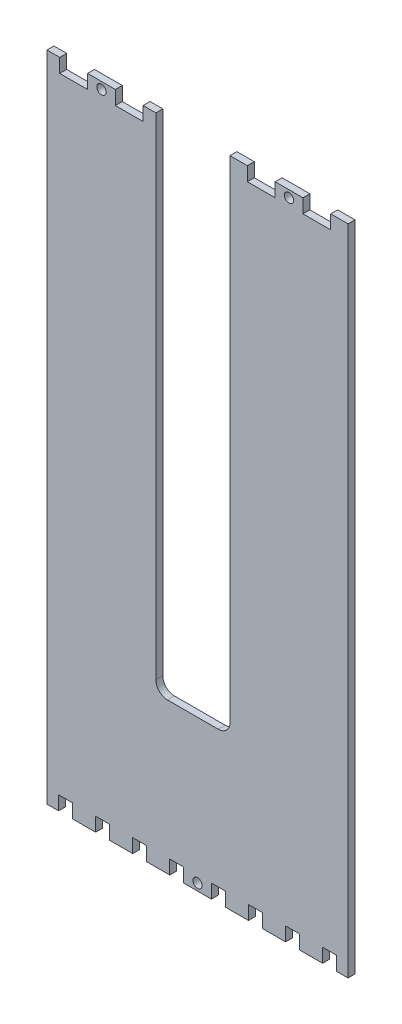
SolidWorks part; units mm, degrees
ref_plane "Plan de face" through (0, 0, 0) normal (0, 0, 1) x (1, 0, 0)
ref_plane "Plan de dessus" through (0, 0, 0) normal (0, 1, 0) x (1, 0, 0)
ref_plane "Plan de droite" through (0, 0, 0) normal (1, 0, 0) x (0, 0, -1)
sketch "Esquisse1" plane through (0, 0, 0) normal (0, 0, 1) x (1, 0, 0)
  line L1 (-46.5414, 49.7197) -> (83.4586, 49.7197)
  line L2 (-46.5414, 49.7197) -> (-46.5414, -232.2803)
  line L3 (-46.5414, -232.2803) -> (83.4586, -232.2803)
  line L4 (83.4586, 49.7197) -> (83.4586, -232.2803)
  dimension "D1" = 130
  dimension "D2" = 282
extrude "Boss.-Extru.1" add sketch "Esquisse1" along normal blind 3
sketch "Esquisse2" plane through (0, 0, 3) normal (0, 0, 1) x (1, 0, 0)
  line L0 (-46.5414, 49.7197) -> (-46.5414, -232.2803) construction
  line L1 (32.4586, -167.2803) -> (0.4586, -167.2803)
  line L2 (32.4586, -167.2803) -> (32.4586, 49.7197)
  line L3 (32.4586, 49.7197) -> (0.4586, 49.7197)
  line L4 (0.4586, -167.2803) -> (0.4586, 49.7197)
  line L5 (83.4586, -232.2803) -> (83.4586, 49.7197) construction
  line L6 (-46.5414, -232.2803) -> (83.4586, -232.2803) construction
  line L7 (83.4586, 49.7197) -> (-46.5414, 49.7197) construction
  dimension "D1" = 47
  dimension "D2" = 51
  dimension "D3" = 65
  dimension "D4" = 0
extrude "Enlèv. mat.-Extru.1" cut sketch "Esquisse2" against normal blind 3
fillet "Congé1" radius 5 2 edges at (32.4586, -167.2803, 1.5) (0.4586, -167.2803, 1.5)
sketch "Esquisse3" plane through (0, 0, 3) normal (0, 0, 1) x (1, 0, 0)
  line L0 (-23.0414, 49.7197) -> (-23.0414, 37.8262) construction
  line L1 (0.4586, 49.7197) -> (-46.5414, 49.7197) construction
  line L2 (-29.0414, 46.7197) -> (-17.0414, 46.7197) construction
  line L3 (-29.0414, 49.7197) -> (-41.0414, 49.7197)
  line L4 (-29.0414, 49.7197) -> (-29.0414, 43.7197)
  line L5 (-29.0414, 43.7197) -> (-41.0414, 43.7197)
  line L6 (-41.0414, 49.7197) -> (-41.0414, 43.7197)
  line L7 (-17.0414, 49.7197) -> (-5.0414, 49.7197)
  line L8 (-17.0414, 49.7197) -> (-17.0414, 43.7197)
  line L9 (-17.0414, 43.7197) -> (-5.0414, 43.7197)
  line L10 (-5.0414, 49.7197) -> (-5.0414, 43.7197)
  line L11 (-17.0414, 43.7197) -> (109.581, 43.7197) construction
  line L12 (57.9586, 49.7197) -> (57.9586, 43.7197) construction
  line L13 (83.4586, 49.7197) -> (32.4586, 49.7197) construction
  line L14 (51.9586, 46.7197) -> (63.9586, 46.7197) construction
  line L15 (51.9586, 49.7197) -> (39.9586, 49.7197)
  line L16 (51.9586, 49.7197) -> (51.9586, 43.7197)
  line L17 (51.9586, 43.7197) -> (39.9586, 43.7197)
  line L18 (39.9586, 49.7197) -> (39.9586, 43.7197)
  line L19 (63.9586, 49.7197) -> (75.9586, 49.7197)
  line L20 (63.9586, 49.7197) -> (63.9586, 43.7197)
  line L21 (63.9586, 43.7197) -> (75.9586, 43.7197)
  line L22 (75.9586, 49.7197) -> (75.9586, 43.7197)
  line L23 (18.4586, -232.2803) -> (18.4586, -214.6987) construction
  line L24 (-46.5414, -232.2803) -> (83.4586, -232.2803) construction
  line L25 (-46.5414, -226.2803) -> (83.4586, -226.2803) construction
  line L26 (-46.5414, 49.7197) -> (-46.5414, -232.2803) construction
  line L27 (83.4586, -232.2803) -> (83.4586, 49.7197) construction
  line L28 (12.4586, -229.2803) -> (24.4586, -229.2803) construction
  line L29 (12.4586, -232.2803) -> (6.4586, -232.2803)
  line L30 (12.4586, -232.2803) -> (12.4586, -226.2803)
  line L31 (12.4586, -226.2803) -> (6.4586, -226.2803)
  line L32 (6.4586, -232.2803) -> (6.4586, -226.2803)
  line L33 (-3.5414, -232.2803) -> (-9.5414, -232.2803)
  line L34 (-3.5414, -232.2803) -> (-3.5414, -226.2803)
  line L35 (-3.5414, -226.2803) -> (-9.5414, -226.2803)
  line L36 (-9.5414, -232.2803) -> (-9.5414, -226.2803)
  line L37 (-35.5414, -232.2803) -> (-41.5414, -232.2803)
  line L38 (-35.5414, -232.2803) -> (-35.5414, -226.2803)
  line L39 (-35.5414, -226.2803) -> (-41.5414, -226.2803)
  line L40 (-41.5414, -232.2803) -> (-41.5414, -226.2803)
  line L41 (24.4586, -232.2803) -> (30.4586, -232.2803)
  line L42 (24.4586, -232.2803) -> (24.4586, -226.2803)
  line L43 (24.4586, -226.2803) -> (30.4586, -226.2803)
  line L44 (30.4586, -232.2803) -> (30.4586, -226.2803)
  line L45 (40.4586, -232.2803) -> (46.4586, -232.2803)
  line L46 (40.4586, -232.2803) -> (40.4586, -226.2803)
  line L47 (40.4586, -226.2803) -> (46.4586, -226.2803)
  line L48 (46.4586, -232.2803) -> (46.4586, -226.2803)
  line L49 (78.4586, -232.2803) -> (72.4586, -232.2803)
  line L50 (78.4586, -232.2803) -> (78.4586, -226.2803)
  line L51 (78.4586, -226.2803) -> (72.4586, -226.2803)
  line L52 (72.4586, -232.2803) -> (72.4586, -226.2803)
  line L53 (-19.5414, -226.2803) -> (-25.5414, -226.2803)
  line L54 (-19.5414, -226.2803) -> (-19.5414, -232.2803)
  line L55 (-19.5414, -232.2803) -> (-25.5414, -232.2803)
  line L56 (-25.5414, -226.2803) -> (-25.5414, -232.2803)
  line L57 (62.4586, -226.2803) -> (56.4586, -226.2803)
  line L58 (62.4586, -226.2803) -> (62.4586, -232.2803)
  line L59 (62.4586, -232.2803) -> (56.4586, -232.2803)
  line L60 (56.4586, -226.2803) -> (56.4586, -232.2803)
  circle A0 centre (-23.0414, 46.7197) radius 2
  circle A1 centre (57.9586, 46.7197) radius 2
  circle A2 centre (18.4586, -229.2803) radius 2
  dimension "D6" = 4
  dimension "D10" = 4
  dimension "D27" = 4
  dimension "D1" = 12
  dimension "D2" = 12
  dimension "D3" = 12
  dimension "D4" = 6
  dimension "D5" = 6
  dimension "D7" = 12
  dimension "D8" = 12
  dimension "D9" = 12
  dimension "D11" = 6
  dimension "D12" = 6
  dimension "D13" = 6
  dimension "D14" = 6
  dimension "D15" = 6
  dimension "D16" = 6
  dimension "D17" = 6
  dimension "D18" = 6
  dimension "D19" = 6
  dimension "D20" = 12
  dimension "D21" = 10
  dimension "D22" = 10
  dimension "D23" = 10
  dimension "D24" = 10
  dimension "D25" = 10
  dimension "D26" = 10
extrude "Enlèv. mat.-Extru.2" cut sketch "Esquisse3" against normal blind 3
